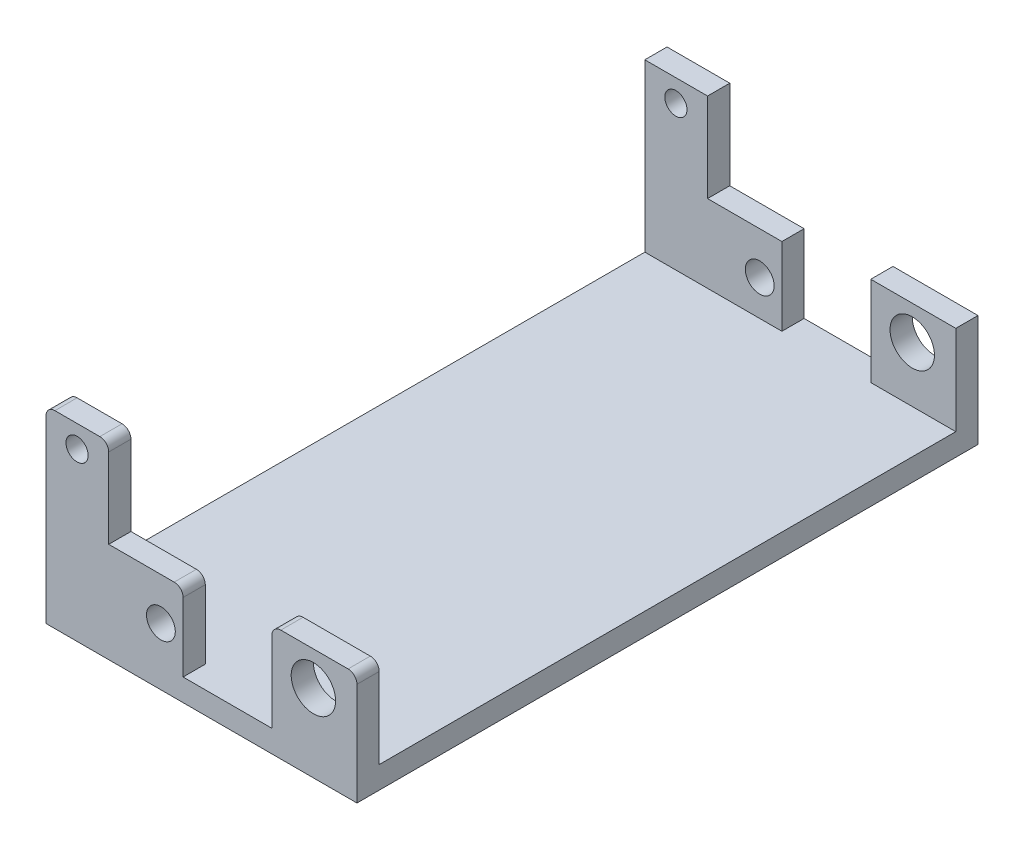
SolidWorks part; units mm, degrees
ref_plane "Front Plane" through (0, 0, 0) normal (0, 0, 1) x (1, 0, 0)
ref_plane "Top Plane" through (0, 0, 0) normal (0, 1, 0) x (1, 0, 0)
ref_plane "Right Plane" through (0, 0, 0) normal (1, 0, 0) x (0, 0, -1)
sketch "Sketch1" plane through (0, 0, 0) normal (0, 0, 1) x (1, 0, 0)
  line L0 (-44.45, 3.175) -> (-44.45, 50.8)
  line L1 (44.45, -3.175) -> (-44.45, -3.175)
  line L2 (44.45, -3.175) -> (44.45, 3.175)
  line L3 (20.1413, 3.175) -> (-5.2614, 3.175)
  line L4 (-44.45, -3.175) -> (-44.45, 3.175)
  line L7 (-44.45, 50.8) -> (-26.5176, 50.8)
  line L8 (-26.5176, 50.8) -> (-26.5176, 25.4)
  line L9 (-26.5176, 25.4) -> (-5.2614, 25.4)
  line L10 (-5.2614, 25.4) -> (-5.2614, 3.175)
  line L11 (-44.45, 50.8) -> (-44.45, 3.175)
  line L12 (44.45, 3.175) -> (44.45, 28.7611)
  line L13 (44.45, 28.7611) -> (20.1413, 28.7611)
  line L14 (20.1413, 28.7611) -> (20.1413, 3.175)
  circle A0 centre (-35.5685, 44.45) radius 3.175
  circle A1 centre (-11.6022, 13.3103) radius 4.1193
  circle A2 centre (31.9955, 19.05) radius 6.35
  point P0 (0, 0)
  point P20 (-11.6022, 13.3103)
  dimension "D5" = 6.35
  dimension "D7" = 12.7
  dimension "D1" = 6.35
  dimension "D2" = 88.9
  dimension "D3" = 17.9324
  dimension "D4" = 22.225
  dimension "D6" = 41.275
  dimension "D8" = 15.875
  dimension "D9" = 67.564
extrude "Boss-Extrude1" add sketch "Sketch1" along normal blind 6.35 contours L13 L14 L3 L10 L9 L8 L7 L0 L4 L1 L2 L12 A2 A1 A0
sketch "Sketch2" plane through (0, 0, 6.35) normal (0, 0, 1) x (1, 0, 0)
  line L1 (-44.45, -3.175) -> (44.45, -3.175)
  line L2 (-44.45, -3.175) -> (-44.45, 3.175)
  line L3 (-44.45, 3.175) -> (44.45, 3.175)
  line L4 (44.45, -3.175) -> (44.45, 3.175)
extrude "Boss-Extrude2" add sketch "Sketch2" against normal blind 177.546
fillet "Fillet1" radius 2.54 5 edges at (44.45, 28.7611, 3.175) (20.1413, 28.7611, 3.175) (-5.2614, 25.4, 3.175) (-44.45, 50.8, 3.175) (-26.5176, 50.8, 3.175)
ref_plane "Plane1" through (0, 0, -82.423) normal (0, 0, 1) x (1, 0, 0)
mirror "Mirror1" about plane through (0, 0, -82.423) normal (0, 0, 1) of "Boss-Extrude1"
